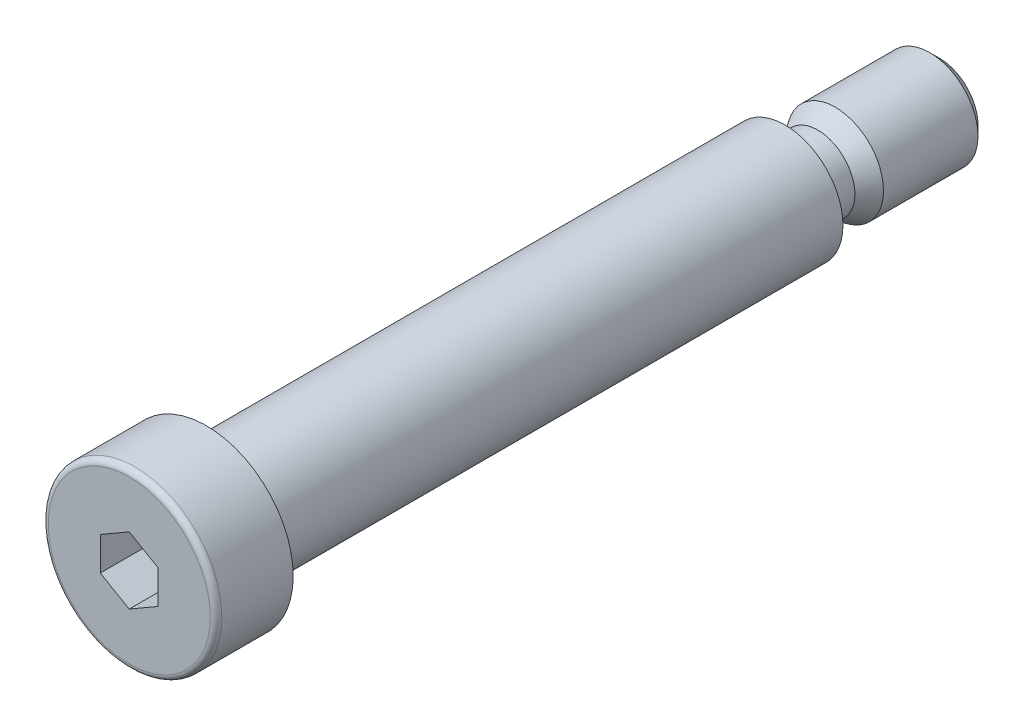
SolidWorks part; units mm, degrees
material "1.0545 (S355N)"
ref_plane "Płaszczyzna przednia" through (0, 0, 0) normal (0, 0, 1) x (1, 0, 0)
ref_plane "Płaszczyzna górna" through (0, 0, 0) normal (0, 1, 0) x (1, 0, 0)
ref_plane "Płaszczyzna prawa" through (0, 0, 0) normal (1, 0, 0) x (0, 0, -1)
sketch "Szkic1" plane through (0, 0, 0) normal (0, 1, 0) x (1, 0, 0)
  line L0 (5, 35.2) -> (3.85, 33.39)
  line L1 (9, -38) -> (-9, -38)
  line L2 (9, -38) -> (9, -30)
  line L3 (9, -30) -> (-9, -30)
  line L4 (-9, -38) -> (-9, -30)
  line L5 (6, -30) -> (-6, -30)
  line L6 (6, -30) -> (6, 30)
  line L7 (6, 30) -> (-6, 30)
  line L8 (-6, -30) -> (-6, 30)
  line L9 (-3.85, 30) -> (3.85, 30)
  line L10 (-3.85, 30) -> (-3.85, 33.39)
  line L11 (-3.85, 33.39) -> (3.85, 33.39)
  line L12 (3.85, 30) -> (3.85, 33.39)
  line L13 (5, 35.2) -> (5, 45)
  line L14 (5, 45) -> (4, 46)
  line L15 (4, 46) -> (-4, 46)
  line L16 (-4, 46) -> (-5, 45)
  line L17 (-5, 45) -> (-5, 35.2)
  line L18 (-5, 35.2) -> (-3.85, 33.39)
  line L19 (5, 35.2) -> (-5, 35.2) construction
  line L20 (5, 45) -> (-5, 45) construction
  line L21 (0, -19.9356) -> (0, 25.6583) construction
  line L22 (0, -38) -> (0, 46)
  point P4 (0, -30)
  point P14 (0, -30)
  point P15 (0, 30)
  point P16 (0, 30)
  point P17 (-6, 0)
  point P23 (0, 35.2)
  point P25 (0, 46)
  point P26 (0, 33.39)
  point P27 (0, 45)
  dimension "D1" = 18
  dimension "D2" = 8
  dimension "D3" = 12
  dimension "l1" = 60
  dimension "D5" = 7.7
  dimension "D6" = 16
  dimension "D7" = 10
  dimension "D8" = 8
  dimension "D9" = 1
  dimension "D10" = 1.81
  dimension "D11" = 9.8
revolve "Obrót1" add sketch "Szkic1" angle 360 about L22
sketch "Szkic2" plane through (0, 0, 38) normal (0, 0, 1) x (1, 0, 0)
  line L1 (3, 1.7321) -> (0, 3.4641)
  line L2 (0, 3.4641) -> (-3, 1.7321)
  line L3 (-3, 1.7321) -> (-3, -1.7321)
  line L4 (-3, -1.7321) -> (0, -3.4641)
  line L5 (0, -3.4641) -> (3, -1.7321)
  line L6 (3, -1.7321) -> (3, 1.7321)
  circle A0 centre (0, 0) radius 3 construction
  dimension "D1" = 6
extrude "Wytnij-wyciągnięcie1" cut sketch "Szkic2" against normal blind 4.9
fillet "Zaokrąglenie1" radius 0.6 1 edges at (9, 0, 38)
